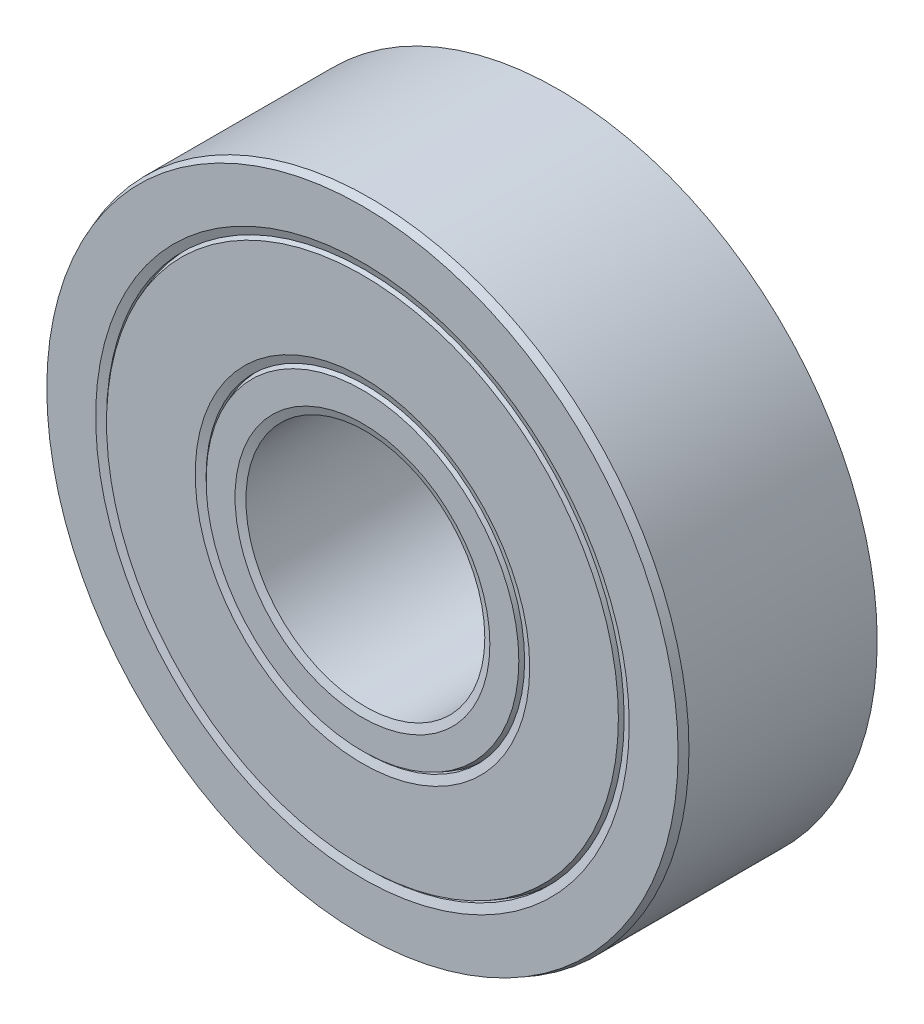
SolidWorks part; units mm, degrees
ref_plane "Front Plane" through (0, 0, 0) normal (0, 0, 1) x (1, 0, 0)
ref_plane "Top Plane" through (0, 0, 0) normal (0, 1, 0) x (1, 0, 0)
ref_plane "Right Plane" through (0, 0, 0) normal (1, 0, 0) x (0, 0, -1)
sketch "Sketch1" plane through (0, 0, 0) normal (0, 0, 1) x (1, 0, 0)
  circle A0 centre (0, 0) radius 3
  circle A1 centre (0, 0) radius 4
  dimension "D1" = 6
  dimension "D2" = 1
extrude "Boss-Extrude1" add sketch "Sketch1" along normal blind 5
sketch "Sketch2" plane through (0, 0, 5) normal (0, 0, 1) x (1, 0, 0)
  circle A0 centre (0, 0) radius 4
  circle A1 centre (0, 0) radius 6.5
  dimension "D1" = 2.5
extrude "Boss-Extrude2" add sketch "Sketch2" against normal blind 5 separate body
sketch "Sketch3" plane through (0, 0, 5) normal (0, 0, 1) x (1, 0, 0)
  circle A0 centre (0, 0) radius 6.5
  circle A1 centre (0, 0) radius 8
  dimension "D1" = 16
  dimension "D2" = 13
extrude "Boss-Extrude3" add sketch "Sketch3" against normal blind 5 separate body
chamfer "Chamfer1" distance 0.2 angle 20 4 edges at (3, 0, 0) (4, 0, 0) (3, 0, 5) (4, 0, 5)
chamfer "Chamfer2" distance 0.2 angle 20 4 edges at (6.5, 0, 0) (4, 0, 0) (6.5, 0, 5) (4, 0, 5)
chamfer "Chamfer3" distance 0.2 angle 20 4 edges at (8, 0, 0) (6.5, 0, 0) (8, 0, 5) (6.5, 0, 5)
equation "\"InnerDia\"= 6mm"
equation "\"OuterDia\"= 16mm"
equation "\"Width\"= 5mm"
equation "\"D1@Sketch1\"=\"InnerDia\""
equation "\"D1@Boss-Extrude1\"=\"Width\""
equation "\"D1@Boss-Extrude2\"=\"Width\""
equation "\"D1@Sketch3\"=\"OuterDia\""
equation "\"D2@Sketch3\"=\"OuterDia\"-3"
equation "\"D1@Boss-Extrude3\"=\"Width\""
